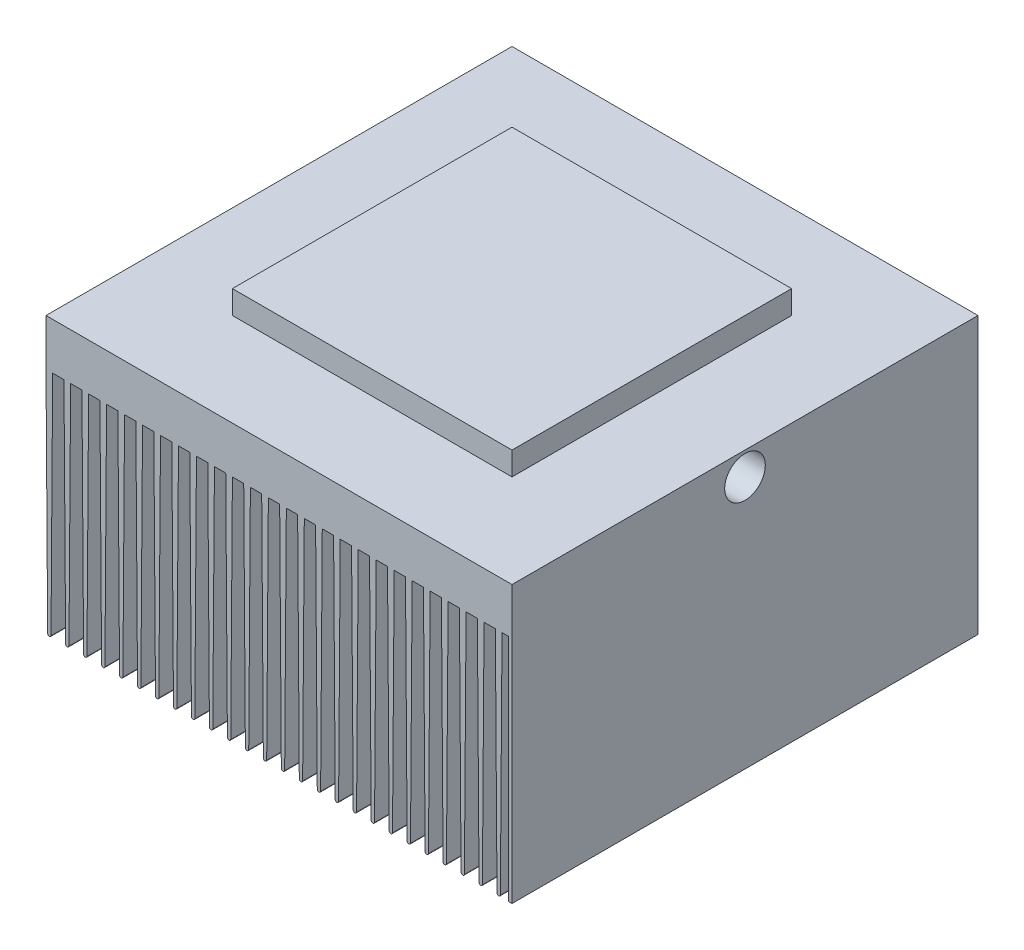
SolidWorks part; units mm, degrees
ref_plane "前视基准面" through (0, 0, 0) normal (0, 0, 1) x (1, 0, 0)
ref_plane "上视基准面" through (0, 0, 0) normal (0, 1, 0) x (1, 0, 0)
ref_plane "右视基准面" through (0, 0, 0) normal (1, 0, 0) x (0, 0, -1)
sketch "草图1" plane through (0, 0, 0) normal (0, 1, 0) x (1, 0, 0)
  line L1 (-35, -35) -> (35, -35)
  line L2 (-35, -35) -> (-35, 35)
  line L3 (-35, 35) -> (35, 35)
  line L4 (35, -35) -> (35, 35)
  line L5 (-35, -35) -> (35, 35) construction
  line L6 (-35, 35) -> (35, -35) construction
  point P0 (0, 0)
  dimension "D1" = 70
  dimension "D2" = 70
extrude "凸台-拉伸1" add sketch "草图1" along normal blind 41.5
sketch "草图2" plane through (0, 41.5, 0) normal (0, 1, 0) x (1, 0, 0)
  line L1 (-21, -21) -> (21, -21)
  line L2 (-21, -21) -> (-21, 21)
  line L3 (-21, 21) -> (21, 21)
  line L4 (21, -21) -> (21, 21)
  line L5 (-21, -21) -> (21, 21) construction
  line L6 (-21, 21) -> (21, -21) construction
  point P0 (0, 0)
  dimension "D1" = 42
extrude "凸台-拉伸2" add sketch "草图2" along normal blind 3.5
sketch "草图3" plane through (0, 0, 35) normal (0, 0, 1) x (1, 0, 0)
  line L0 (-35, 34.5) -> (35, 34.5) construction
  line L1 (-35, 41.5) -> (-35, 0) construction
  line L2 (35, 41.5) -> (35, 0) construction
  line L3 (-35, 41.5) -> (35, 41.5) construction
  line L4 (-35, 34.5) -> (-34.7518, 0.2482)
  line L5 (-35, 0) -> (35, 0) construction
  line L6 (-34.5018, 0) -> (-34.4982, 0)
  line L7 (-34.2482, 0.2482) -> (-34, 34.5)
  line L8 (-34, 34.5) -> (-32.3, 34.5)
  line L9 (-32.3, 34.5) -> (-32.0518, 0.2482)
  line L10 (-31.5482, 0.2482) -> (-31.3, 34.5)
  line L11 (-29.6, 34.5) -> (-29.3518, 0.2482)
  line L12 (-28.8482, 0.2482) -> (-28.6, 34.5)
  line L13 (-26.9, 34.5) -> (-26.6518, 0.2482)
  line L14 (-26.1482, 0.2482) -> (-25.9, 34.5)
  line L15 (-24.2, 34.5) -> (-23.9518, 0.2482)
  line L16 (-23.4482, 0.2482) -> (-23.2, 34.5)
  line L17 (-21.5, 34.5) -> (-21.2518, 0.2482)
  line L18 (-20.7482, 0.2482) -> (-20.5, 34.5)
  line L19 (-18.8, 34.5) -> (-18.5518, 0.2482)
  line L20 (-18.0482, 0.2482) -> (-17.8, 34.5)
  line L21 (-16.1, 34.5) -> (-15.8518, 0.2482)
  line L22 (-15.3482, 0.2482) -> (-15.1, 34.5)
  line L23 (-13.4, 34.5) -> (-13.1518, 0.2482)
  line L24 (-12.6482, 0.2482) -> (-12.4, 34.5)
  line L25 (-10.7, 34.5) -> (-10.4518, 0.2482)
  line L26 (-9.9482, 0.2482) -> (-9.7, 34.5)
  line L27 (-8, 34.5) -> (-7.7518, 0.2482)
  line L28 (-7.2482, 0.2482) -> (-7, 34.5)
  line L29 (-5.3, 34.5) -> (-5.0518, 0.2482)
  line L30 (-4.5482, 0.2482) -> (-4.3, 34.5)
  line L31 (-2.6, 34.5) -> (-2.3518, 0.2482)
  line L32 (-1.8482, 0.2482) -> (-1.6, 34.5)
  line L33 (0.1, 34.5) -> (0.3482, 0.2482)
  line L34 (0.8518, 0.2482) -> (1.1, 34.5)
  line L35 (2.8, 34.5) -> (3.0482, 0.2482)
  line L36 (3.5518, 0.2482) -> (3.8, 34.5)
  line L37 (5.5, 34.5) -> (5.7482, 0.2482)
  line L38 (6.2518, 0.2482) -> (6.5, 34.5)
  line L39 (8.2, 34.5) -> (8.4482, 0.2482)
  line L40 (8.9518, 0.2482) -> (9.2, 34.5)
  line L41 (10.9, 34.5) -> (11.1482, 0.2482)
  line L42 (11.6518, 0.2482) -> (11.9, 34.5)
  line L43 (13.6, 34.5) -> (13.8482, 0.2482)
  line L44 (14.3518, 0.2482) -> (14.6, 34.5)
  line L45 (16.3, 34.5) -> (16.5482, 0.2482)
  line L46 (17.0518, 0.2482) -> (17.3, 34.5)
  line L47 (19, 34.5) -> (19.2482, 0.2482)
  line L48 (19.7518, 0.2482) -> (20, 34.5)
  line L49 (21.7, 34.5) -> (21.9482, 0.2482)
  line L50 (22.4518, 0.2482) -> (22.7, 34.5)
  line L51 (24.4, 34.5) -> (24.6482, 0.2482)
  line L52 (25.1518, 0.2482) -> (25.4, 34.5)
  line L53 (27.1, 34.5) -> (27.3482, 0.2482)
  line L54 (27.8518, 0.2482) -> (28.1, 34.5)
  line L55 (29.8, 34.5) -> (30.0482, 0.2482)
  line L56 (30.5518, 0.2482) -> (30.8, 34.5)
  line L57 (32.5, 34.5) -> (32.7482, 0.2482)
  line L58 (33.2518, 0.2482) -> (33.5, 34.5)
  line L59 (34.5, 34.5) -> (34.5, 0)
  line L60 (-31.3, 34.5) -> (-29.6, 34.5)
  line L61 (-28.6, 34.5) -> (-26.9, 34.5)
  line L62 (-25.9, 34.5) -> (-24.2, 34.5)
  line L63 (-23.2, 34.5) -> (-21.5, 34.5)
  line L64 (-20.5, 34.5) -> (-18.8, 34.5)
  line L65 (-17.8, 34.5) -> (-16.1, 34.5)
  line L66 (-15.1, 34.5) -> (-13.4, 34.5)
  line L67 (-12.4, 34.5) -> (-10.7, 34.5)
  line L68 (-9.7, 34.5) -> (-8, 34.5)
  line L69 (-7, 34.5) -> (-5.3, 34.5)
  line L70 (-4.3, 34.5) -> (-2.6, 34.5)
  line L71 (-1.6, 34.5) -> (0.1, 34.5)
  line L72 (1.1, 34.5) -> (2.8, 34.5)
  line L73 (3.8, 34.5) -> (5.5, 34.5)
  line L74 (6.5, 34.5) -> (8.2, 34.5)
  line L75 (9.2, 34.5) -> (10.9, 34.5)
  line L76 (11.9, 34.5) -> (13.6, 34.5)
  line L77 (14.6, 34.5) -> (16.3, 34.5)
  line L78 (17.3, 34.5) -> (19, 34.5)
  line L79 (20, 34.5) -> (21.7, 34.5)
  line L80 (22.7, 34.5) -> (24.4, 34.5)
  line L81 (25.4, 34.5) -> (27.1, 34.5)
  line L82 (28.1, 34.5) -> (29.8, 34.5)
  line L83 (30.8, 34.5) -> (32.5, 34.5)
  line L84 (33.5, 34.5) -> (34.5, 34.5)
  line L85 (33.5, 34.5) -> (35.2, 34.5) [skipped]
  line L86 (34.5, 0) -> (-34.5018, 0)
  line L87 (34.5, 0) -> (-35, 0)
  arc A0 (-34.2482, 0.2482) -> (-34.4982, 0) centre (-34.4982, 0.25) cw
  arc A1 (-34.5018, 0) -> (-34.7518, 0.2482) centre (-34.5018, 0.25) cw
  arc A2 (-31.5482, 0.2482) -> (-31.7982, 0) centre (-31.7982, 0.25) cw
  arc A3 (-31.8018, 0) -> (-32.0518, 0.2482) centre (-31.8018, 0.25) cw
  arc A4 (-28.8482, 0.2482) -> (-29.0982, 0) centre (-29.0982, 0.25) cw
  arc A5 (-29.1018, 0) -> (-29.3518, 0.2482) centre (-29.1018, 0.25) cw
  arc A6 (-26.1482, 0.2482) -> (-26.3982, 0) centre (-26.3982, 0.25) cw
  arc A7 (-26.4018, 0) -> (-26.6518, 0.2482) centre (-26.4018, 0.25) cw
  arc A8 (-23.4482, 0.2482) -> (-23.6982, 0) centre (-23.6982, 0.25) cw
  arc A9 (-23.7018, 0) -> (-23.9518, 0.2482) centre (-23.7018, 0.25) cw
  arc A10 (-20.7482, 0.2482) -> (-20.9982, 0) centre (-20.9982, 0.25) cw
  arc A11 (-21.0018, 0) -> (-21.2518, 0.2482) centre (-21.0018, 0.25) cw
  arc A12 (-18.0482, 0.2482) -> (-18.2982, 0) centre (-18.2982, 0.25) cw
  arc A13 (-18.3018, 0) -> (-18.5518, 0.2482) centre (-18.3018, 0.25) cw
  arc A14 (-15.3482, 0.2482) -> (-15.5982, 0) centre (-15.5982, 0.25) cw
  arc A15 (-15.6018, 0) -> (-15.8518, 0.2482) centre (-15.6018, 0.25) cw
  arc A16 (-12.6482, 0.2482) -> (-12.8982, 0) centre (-12.8982, 0.25) cw
  arc A17 (-12.9018, 0) -> (-13.1518, 0.2482) centre (-12.9018, 0.25) cw
  arc A18 (-9.9482, 0.2482) -> (-10.1982, 0) centre (-10.1982, 0.25) cw
  arc A19 (-10.2018, 0) -> (-10.4518, 0.2482) centre (-10.2018, 0.25) cw
  arc A20 (-7.2482, 0.2482) -> (-7.4982, 0) centre (-7.4982, 0.25) cw
  arc A21 (-7.5018, 0) -> (-7.7518, 0.2482) centre (-7.5018, 0.25) cw
  arc A22 (-4.5482, 0.2482) -> (-4.7982, 0) centre (-4.7982, 0.25) cw
  arc A23 (-4.8018, 0) -> (-5.0518, 0.2482) centre (-4.8018, 0.25) cw
  arc A24 (-1.8482, 0.2482) -> (-2.0982, 0) centre (-2.0982, 0.25) cw
  arc A25 (-2.1018, 0) -> (-2.3518, 0.2482) centre (-2.1018, 0.25) cw
  arc A26 (0.8518, 0.2482) -> (0.6018, 0) centre (0.6018, 0.25) cw
  arc A27 (0.5982, 0) -> (0.3482, 0.2482) centre (0.5982, 0.25) cw
  arc A28 (3.5518, 0.2482) -> (3.3018, 0) centre (3.3018, 0.25) cw
  arc A29 (3.2982, 0) -> (3.0482, 0.2482) centre (3.2982, 0.25) cw
  arc A30 (6.2518, 0.2482) -> (6.0018, 0) centre (6.0018, 0.25) cw
  arc A31 (5.9982, 0) -> (5.7482, 0.2482) centre (5.9982, 0.25) cw
  arc A32 (8.9518, 0.2482) -> (8.7018, 0) centre (8.7018, 0.25) cw
  arc A33 (8.6982, 0) -> (8.4482, 0.2482) centre (8.6982, 0.25) cw
  arc A34 (11.6518, 0.2482) -> (11.4018, 0) centre (11.4018, 0.25) cw
  arc A35 (11.3982, 0) -> (11.1482, 0.2482) centre (11.3982, 0.25) cw
  arc A36 (14.3518, 0.2482) -> (14.1018, 0) centre (14.1018, 0.25) cw
  arc A37 (14.0982, 0) -> (13.8482, 0.2482) centre (14.0982, 0.25) cw
  arc A38 (17.0518, 0.2482) -> (16.8018, 0) centre (16.8018, 0.25) cw
  arc A39 (16.7982, 0) -> (16.5482, 0.2482) centre (16.7982, 0.25) cw
  arc A40 (19.7518, 0.2482) -> (19.5018, 0) centre (19.5018, 0.25) cw
  arc A41 (19.4982, 0) -> (19.2482, 0.2482) centre (19.4982, 0.25) cw
  arc A42 (22.4518, 0.2482) -> (22.2018, 0) centre (22.2018, 0.25) cw
  arc A43 (22.1982, 0) -> (21.9482, 0.2482) centre (22.1982, 0.25) cw
  arc A44 (25.1518, 0.2482) -> (24.9018, 0) centre (24.9018, 0.25) cw
  arc A45 (24.8982, 0) -> (24.6482, 0.2482) centre (24.8982, 0.25) cw
  arc A46 (27.8518, 0.2482) -> (27.6018, 0) centre (27.6018, 0.25) cw
  arc A47 (27.5982, 0) -> (27.3482, 0.2482) centre (27.5982, 0.25) cw
  arc A48 (30.5518, 0.2482) -> (30.3018, 0) centre (30.3018, 0.25) cw
  arc A49 (30.2982, 0) -> (30.0482, 0.2482) centre (30.2982, 0.25) cw
  arc A50 (33.2518, 0.2482) -> (33.0018, 0) centre (33.0018, 0.25) cw
  arc A51 (32.9982, 0) -> (32.7482, 0.2482) centre (32.9982, 0.25) cw
  point P16 (-34.25, 0)
  point P19 (-34.75, 0)
  line M7 (-35, 0) -> (35, 0)
  dimension "D5" = 0.25
  dimension "D1" = 7
  dimension "D2" = 1
  dimension "D3" = 0.5
  dimension "D4" = 1.7
  dimension "D7" = 0.5
  dimension "D6" = 26
  dimension "D8" = 26
extrude "切除-拉伸1" cut sketch "草图3" against normal through all contours A3 L9 L8 L7 A0 M7 | L87 A5 L11 L60 L10 A2 | A7 L13 L61 L12 A4 M7 | L87 A9 L15 L62 L14 A6 | A11 L17 L63 L16 A8 M7 | L87 A13 L19 L64 L18 A10 | A15 L21 L65 L20 A12 M7 | L87 A17 L23 L66 L22 A14 | A19 L25 L67 L24 A16 M7 | L87 A21 L27 L68 L26 A18 | A23 L29 L69 L28 A20 M7 | L87 A25 L31 L70 L30 A22 | A27 L33 L71 L32 A24 M7 | L87 A29 L35 L72 L34 A26 | A31 L37 L73 L36 A28 M7 | L87 A33 L39 L74 L38 A30 | A35 L41 L75 L40 A32 M7 | L87 A37 L43 L76 L42 A34 | A39 L45 L77 L44 A36 M7 | A43 L49 L79 L48 A40 M7 | L87 A45 L51 L80 L50 A42 | L87 A41 L47 L78 L46 A38 | A47 L53 L81 L52 A44 M7 | L87 A49 L55 L82 L54 A46 | A51 L57 L83 L56 A48 M7 | L58 A50 L87 L59 L84
sketch "草图4" plane through (0, 0, 35) normal (0, 0, 1) x (1, 0, 0)
  line L0 (-35, 0) -> (-35, 34.5)
  line L1 (-35, 34.5) -> (-34.75, 0)
  line L2 (-34.75, 0) -> (-35, 0)
extrude "切除-拉伸2" cut sketch "草图4" against normal through all
fillet "圆角2" radius 0.25 1 edges at (-34.75, 0, 0)
sketch "草图5" plane through (35, 0, 0) normal (1, 0, 0) x (0, 0, -1)
  line L0 (-35, 41.5) -> (35, 41.5) construction
  circle A0 centre (0, 38) radius 3.05
  point P2 (0, 0)
  dimension "D1" = 6.1
  dimension "D2" = 3.5
extrude "切除-拉伸3" cut sketch "草图5" against normal blind 52
